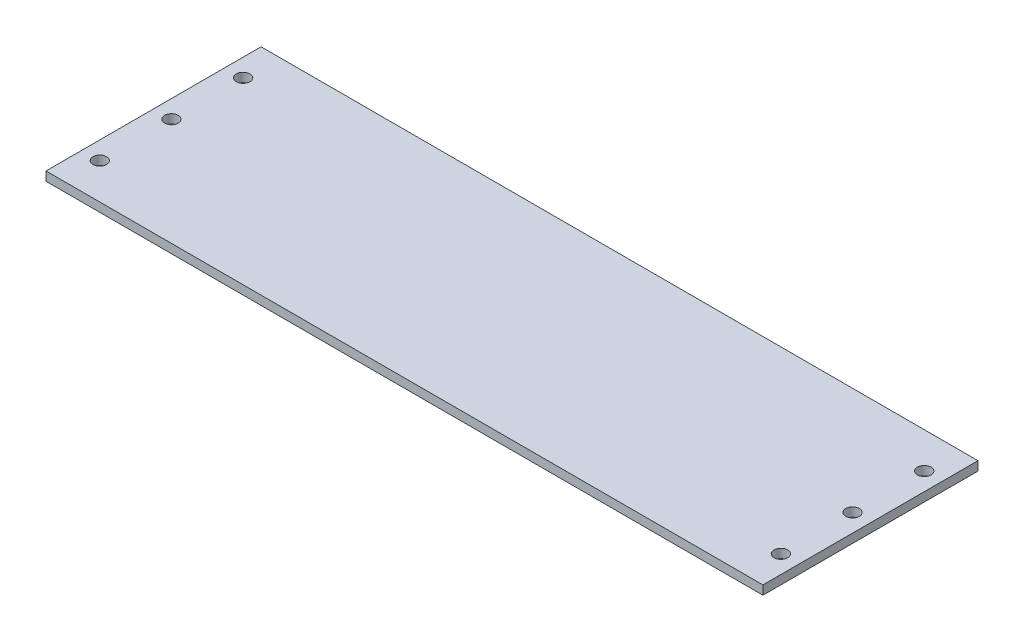
SolidWorks part; units mm, degrees
ref_plane "Front Plane" through (0, 0, 0) normal (0, 0, 1) x (1, 0, 0)
ref_plane "Top Plane" through (0, 0, 0) normal (0, 1, 0) x (1, 0, 0)
ref_plane "Right Plane" through (0, 0, 0) normal (1, 0, 0) x (0, 0, -1)
sketch "Sketch1" plane through (0, 0, 0) normal (0, 1, 0) x (1, 0, 0)
  line L0 (0, 38.1) -> (254, 38.1) construction
  line L1 (0, 0) -> (254, 0)
  line L2 (0, 0) -> (0, 76.2)
  line L3 (0, 76.2) -> (254, 76.2)
  line L4 (254, 0) -> (254, 76.2)
  line L5 (0, 63.5) -> (6.35, 63.5) construction
  line L6 (6.35, 63.5) -> (6.35, 12.7) construction
  line L7 (127, 76.2) -> (127, 0) construction
  circle A0 centre (6.35, 63.5) radius 2.413
  circle A1 centre (6.35, 38.1) radius 2.413
  circle A2 centre (6.35, 12.7) radius 2.413
  circle A3 centre (247.65, 12.7) radius 2.413
  circle A4 centre (247.65, 38.1) radius 2.413
  circle A5 centre (247.65, 63.5) radius 2.413
  dimension "D3" = 4.826
  dimension "D6" = 12.7
  dimension "D1" = 254
  dimension "D2" = 76.2
  dimension "D5" = 6.35
  dimension "D4" = 3
extrude "Boss-Extrude1" add sketch "Sketch1" along normal blind 3.175
